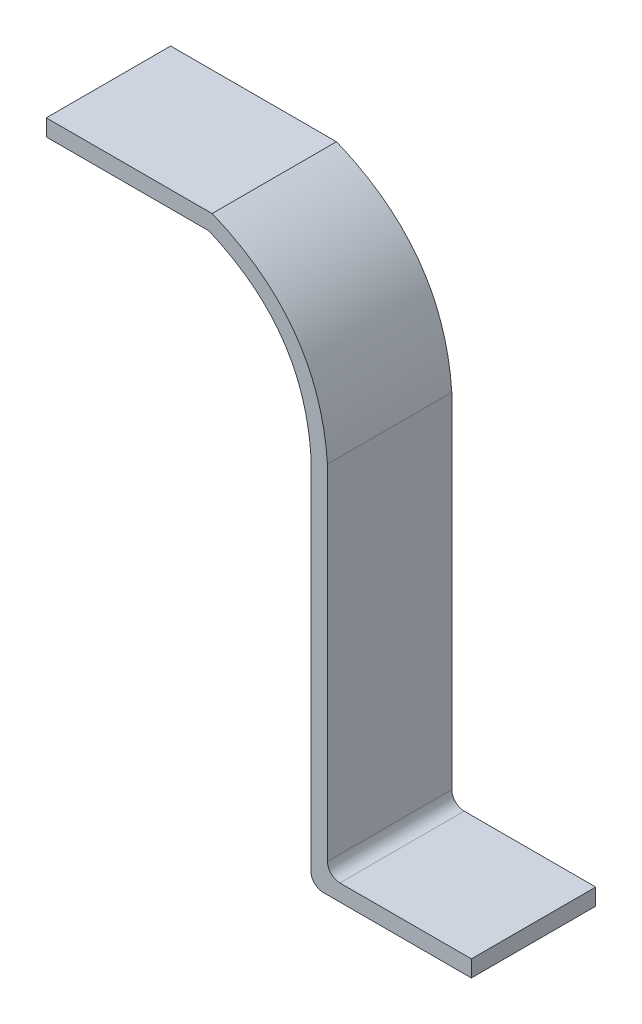
SolidWorks part; units mm, degrees
ref_plane "Front" through (0, 0, 0) normal (0, 0, 1) x (1, 0, 0)
ref_plane "Top" through (0, 0, 0) normal (0, 1, 0) x (1, 0, 0)
ref_plane "Right" through (0, 0, 0) normal (1, 0, 0) x (0, 0, -1)
sketch "Sketch1" plane through (0, 0, 0) normal (0, 0, 1) x (1, 0, 0)
  line L0 (-40, 38.5569) -> (0, 38.5569)
  line L1 (27.8246, 0.1312) -> (27.8246, -82.8688)
  line L2 (-40, 34.5569) -> (-0.7963, 34.5569)
  line L3 (23.8246, -0.01) -> (23.8246, -86.8688)
  line L4 (-40, 38.5569) -> (-40, 34.5569)
  line L5 (27.8246, -89.8688) -> (26.8246, -89.8688)
  line L6 (30.8246, -85.8688) -> (62.5413, -85.8688)
  line L7 (62.5413, -85.8688) -> (62.5413, -89.8688)
  line L8 (62.5413, -89.8688) -> (27.8246, -89.8688)
  line L9 (27.8246, 0.1312) -> (27.8246, -89.8688) construction
  line L10 (23.8246, -0.01) -> (23.8246, -89.8688) construction
  arc A0 (23.8246, -86.8688) -> (26.8246, -89.8688) centre (26.8246, -86.8688) ccw
  arc A1 (27.8246, -82.8688) -> (30.8246, -85.8688) centre (30.8246, -82.8688) ccw
  spline S0 degree 2 poles (0, 38.5569) (25.8853, 28.0238) (27.8246, 0.1312) knots 0 0 0 1 1 1
  spline S1 degree 1 poles (-0.7963, 34.5569) (23.8246, -0.01) knots 0 0 1 1 construction
  spline S2 degree 3 poles (-0.7963, 34.5569) (-0.3131, 34.3527) (0.6547, 33.9276) (2.5094, 33.0474) (4.7164, 31.875) (7.1769, 30.3596) (10.2158, 28.1942) (13.569, 25.2181) (16.9172, 21.2061) (19.6216, 16.7245) (21.3516, 12.5652) (22.4195, 8.9644) (23.0602, 6.1247) (23.4591, 3.6371) (23.6955, 1.5802) (23.7867, 0.5178) (23.8246, -0.01) knots 0.014798 0.014798 0.014798 0.014798 0.045504 0.07621 0.137621 0.199033 0.260445 0.383269 0.506093 0.628916 0.75174 0.813152 0.874564 0.935976 0.966682 0.997388 0.997388 0.997388 0.997388
  dimension "D5" = 3
  dimension "D2" = 90
  dimension "D3" = 40
  dimension "D4" = 4
  dimension "D1" = 4
extrude "Boss-Extrude1" add sketch "Sketch1" along normal blind 30
